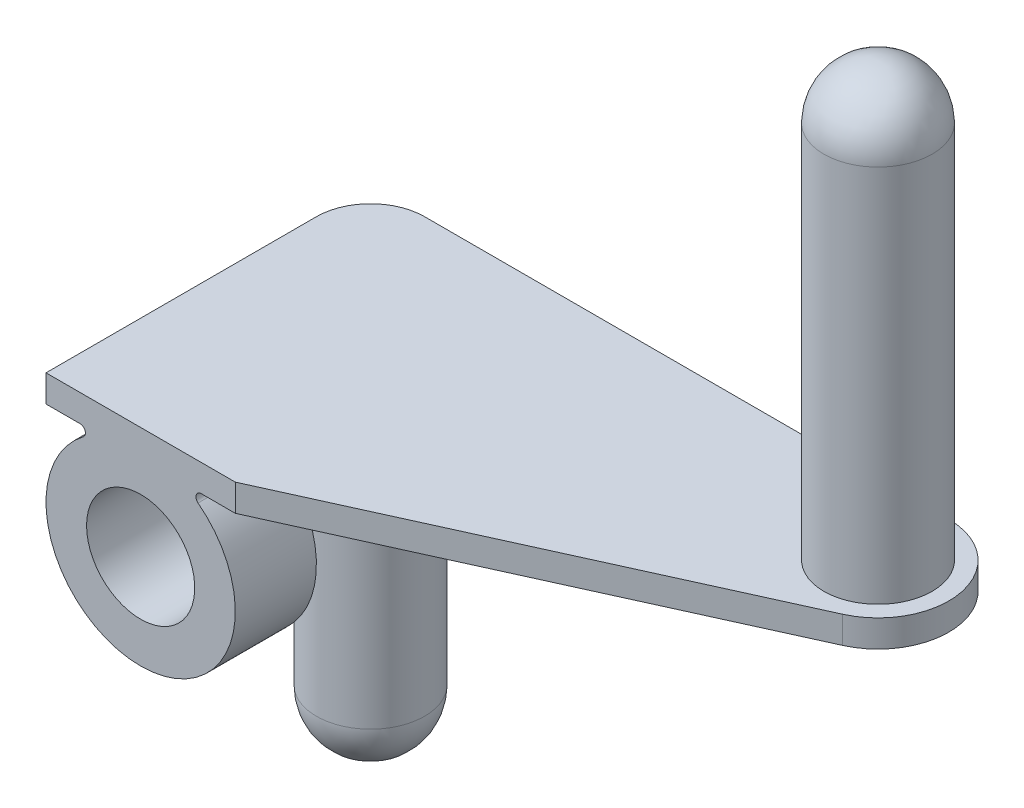
SolidWorks part; units mm, degrees
ref_plane "Front Plane" through (0, 0, 0) normal (0, 0, 1) x (1, 0, 0)
ref_plane "Top Plane" through (0, 0, 0) normal (0, 1, 0) x (1, 0, 0)
ref_plane "Right Plane" through (0, 0, 0) normal (1, 0, 0) x (0, 0, -1)
sketch "Sketch1" plane through (0, 0, 0) normal (0, 1, 0) x (1, 0, 0)
  circle A0 centre (-38.3909, 0) radius 2
extrude "Boss-Extrude1" add sketch "Sketch1" against normal blind 16
fillet "Fillet1" radius 2 1 edges at (-38.3909, -16, 2)
sketch "Sketch2" plane through (0, 0, 0) normal (0, 1, 0) x (1, 0, 0)
  line L0 (-40.3909, 0) -> (-40.3909, 10)
  line L1 (-40.3909, 10) -> (-33.3909, 10)
  line L2 (-33.3909, 10) -> (-17.9286, 3.0008)
  line L3 (-19.0078, -2) -> (-38.3909, -2)
  line L4 (-16.3909, 5.6385) -> (-16.3909, -2.6543) construction
  circle A0 centre (-38.3909, 0) radius 2 construction
  arc A1 (-17.9286, 3.0008) -> (-19.0078, -2) centre (-19.0078, 0.6168) cw
  arc A2 (-38.3909, -2) -> (-40.3909, 0) centre (-38.3909, 0) cw
  dimension "D1" = 7
  dimension "D2" = 24
  dimension "D3" = 12
extrude "Boss-Extrude2" add sketch "Sketch2" against normal blind 1
sketch "Sketch3" plane through (0, 0, 0) normal (0, 1, 0) x (1, 0, 0)
  arc A0 (-19.0078, -2) -> (-17.9286, 3.0008) centre (-19.0078, 0.6168) ccw construction
  arc A1 (-19.0078, -2) -> (-17.9286, 3.0008) centre (-19.0078, 0.6168) ccw
  circle A2 centre (-19.0078, 0.6168) radius 2
extrude "Boss-Extrude3" add sketch "Sketch3" along normal blind 16 contours A2
fillet "Fillet2" radius 2 1 edges at (-19.0078, 16, 1.3832)
sketch "Sketch4" plane through (0, 0, -10) normal (0, 0, -1) x (-1, 0, 0)
  line L0 (33.3909, -1) -> (40.3909, -1) construction
  line L1 (33.3909, -1) -> (40.3909, -1)
  circle A0 centre (36.8909, -4.142) radius 3.5
  point P5 (36.8909, -1)
extrude "Extrude-Thin1" add sketch "Sketch4" against normal blind 3 thin contours L1 A0
fillet "Fillet3" radius 0.2 2 edges at (-38.4329, -1, -8.5) (-35.349, -1, -8.5)
sketch "Sketch5" plane through (0, 0, -10) normal (0, 0, -1) x (-1, 0, 0)
  arc A0 (34.7685, -1.359) -> (39.0134, -1.359) centre (36.8909, -4.142) ccw construction
  arc A1 (34.7685, -1.359) -> (39.0134, -1.359) centre (36.8909, -4.142) ccw
  circle A2 centre (36.8909, -4.142) radius 2
extrude "Cut-Extrude1" cut sketch "Sketch5" against normal blind 6 contours A2
ref_plane "Plane1" through (0, 0, 10) normal (0, 0, 1) x (1, 0, 0)
mirror "Mirror1" about plane through (0, 0, 10) normal (0, 0, 1)
sketch "Sketch6" plane through (0, 0, 0) normal (0, 1, 0) x (1, 0, 0)
  line L1 (-41.4853, 12.3241) -> (-13.6848, 12.3241)
  line L2 (-41.4853, 12.3241) -> (-41.4853, -4.2218)
  line L3 (-41.4853, -4.2218) -> (-13.6848, -4.2218)
  line L4 (-13.6848, 12.3241) -> (-13.6848, -4.2218)
extrude "Cut-Extrude2" cut sketch "Sketch6" against normal through all both and the other way through all
